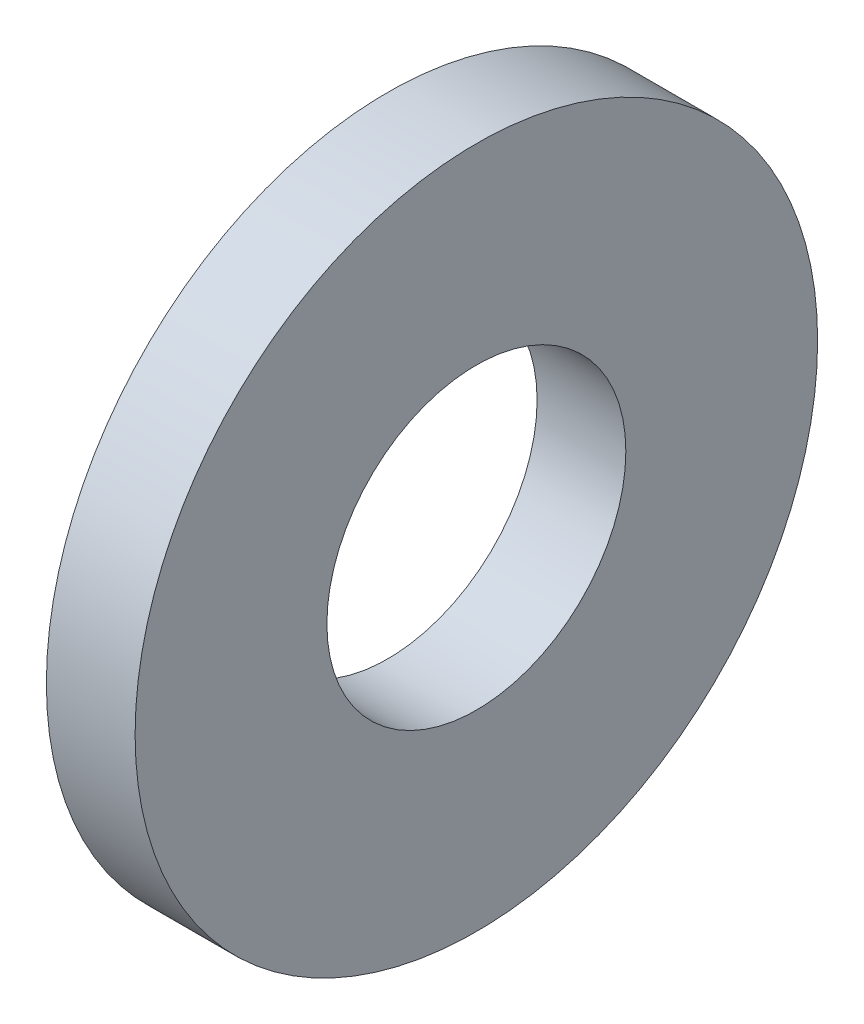
SolidWorks part; units mm, degrees
ref_plane "Front Plane" through (0, 0, 0) normal (0, 0, 1) x (1, 0, 0)
ref_plane "Top Plane" through (0, 0, 0) normal (0, 1, 0) x (1, 0, 0)
ref_plane "Right Plane" through (0, 0, 0) normal (1, 0, 0) x (0, 0, -1)
sketch "Sketch1" plane through (0, 0, 0) normal (1, 0, 0) x (0, 0, -1)
  circle A0 centre (0, 0) radius 6.35
  circle A1 centre (0, 0) radius 2.7813
  dimension "OD" = 12.7
  dimension "ID" = 5.5626
extrude "Boss-Extrude1" add sketch "Sketch1" along normal blind 1.651
